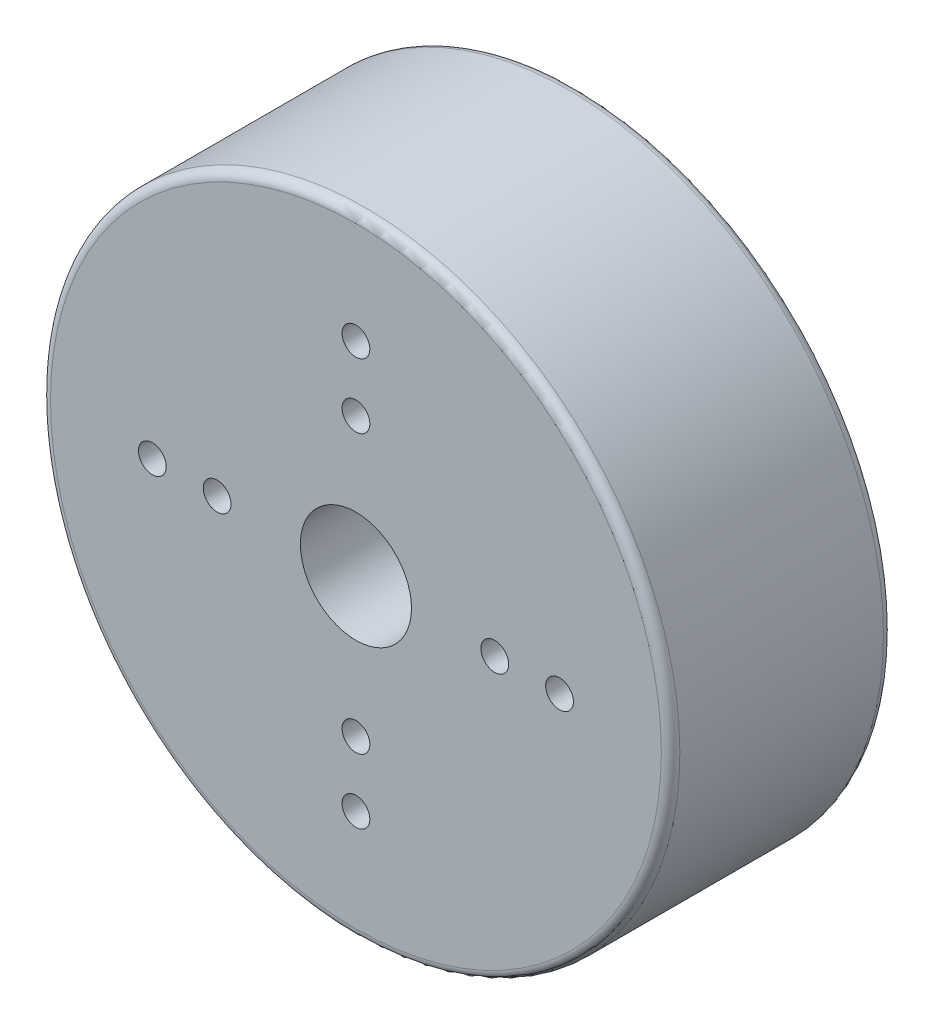
SolidWorks part; units mm, degrees
ref_plane "前视基准面" through (0, 0, 0) normal (0, 0, 1) x (1, 0, 0)
ref_plane "上视基准面" through (0, 0, 0) normal (0, 1, 0) x (1, 0, 0)
ref_plane "右视基准面" through (0, 0, 0) normal (1, 0, 0) x (0, 0, -1)
sketch "草图1" plane through (0, 0, 0) normal (0, 0, 1) x (1, 0, 0)
  circle A0 centre (0, 0) radius 34
extrude "凸台-拉伸1" add sketch "草图1" along normal blind 24 contours A0
sketch "草图2" plane through (0, 0, 0) normal (0, 0, -1) x (-1, 0, 0)
  circle A0 centre (0, 0) radius 7
extrude "凸台-拉伸2" add sketch "草图2" along normal blind 1.1
sketch "草图3" plane through (0, 0, -1.1) normal (0, 0, -1) x (-1, 0, 0)
  circle A0 centre (0, 0) radius 6
extrude "切除-拉伸1" cut sketch "草图3" against normal blind 28.1
sketch "草图4" plane through (0, 0, 24) normal (0, 0, 1) x (1, 0, 0)
  circle A2 centre (0, 22) radius 1.5
  circle A3 centre (0, -22) radius 1.5
  circle A4 centre (-22, 0) radius 1.5
  circle A5 centre (22, 0) radius 1.5
  circle A6 centre (0, 15) radius 1.5
  circle A7 centre (-15, 0) radius 1.5
  circle A8 centre (15, 0) radius 1.5
  circle A9 centre (0, -15) radius 1.5
extrude "切除-拉伸2" cut sketch "草图4" against normal blind 28.1
fillet "圆角2" radius 1 1 edges at (34, 0, 0)
fillet "圆角3" radius 1 1 edges at (34, 0, 24)
